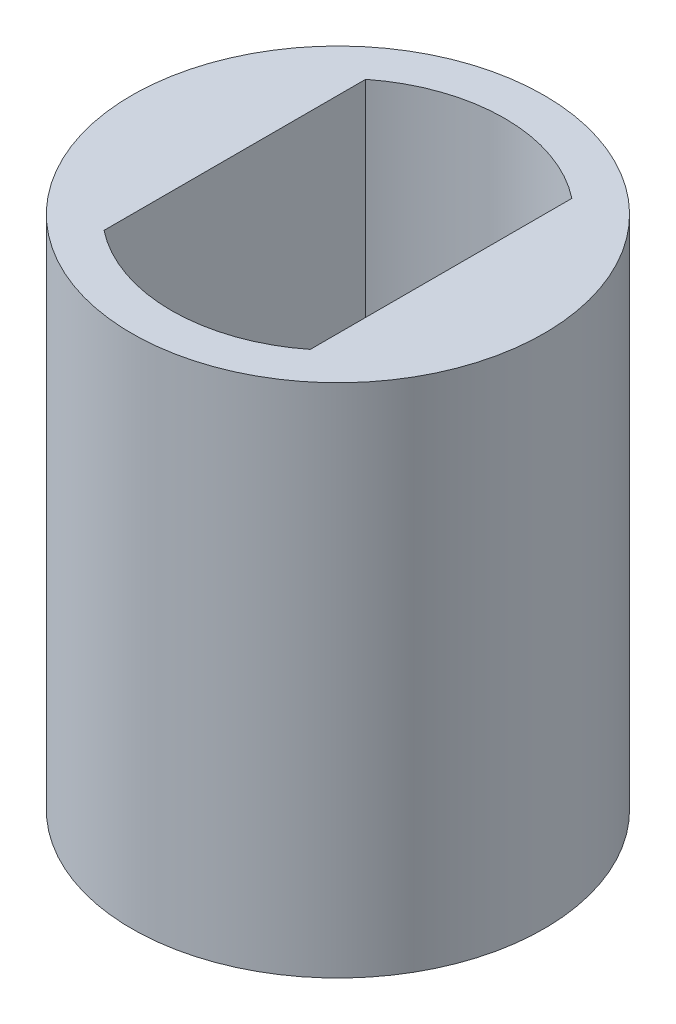
SolidWorks part; units mm, degrees
ref_plane "Plano frontal" through (0, 0, 0) normal (0, 0, 1) x (1, 0, 0)
ref_plane "Plano superior" through (0, 0, 0) normal (0, 1, 0) x (1, 0, 0)
ref_plane "Plano direito" through (0, 0, 0) normal (1, 0, 0) x (0, 0, -1)
sketch "Esboço1" plane through (0, 0, 0) normal (0, 1, 0) x (1, 0, 0)
  line L0 (0, 2.6) -> (0, -2.6) construction
  line L1 (1.3, 2.2517) -> (1.3, -2.2517)
  line L2 (-1.3, 2.2517) -> (-1.3, -2.2517)
  circle A0 centre (0, 0) radius 2.6
  circle A1 centre (0, 0) radius 2.1
  point P6 (0, 0.2359)
extrude "Ressalto-extrusão2" add sketch "Esboço1" along normal blind 6.5 contours L2 A1 | A1 L2 A0 | L0 A1 L2 A0 | A1 L0 A0 L1 | A1 L1 A0 | A0 L0 A1 L1 | L0 A0 L2 A1 | L1 A1
